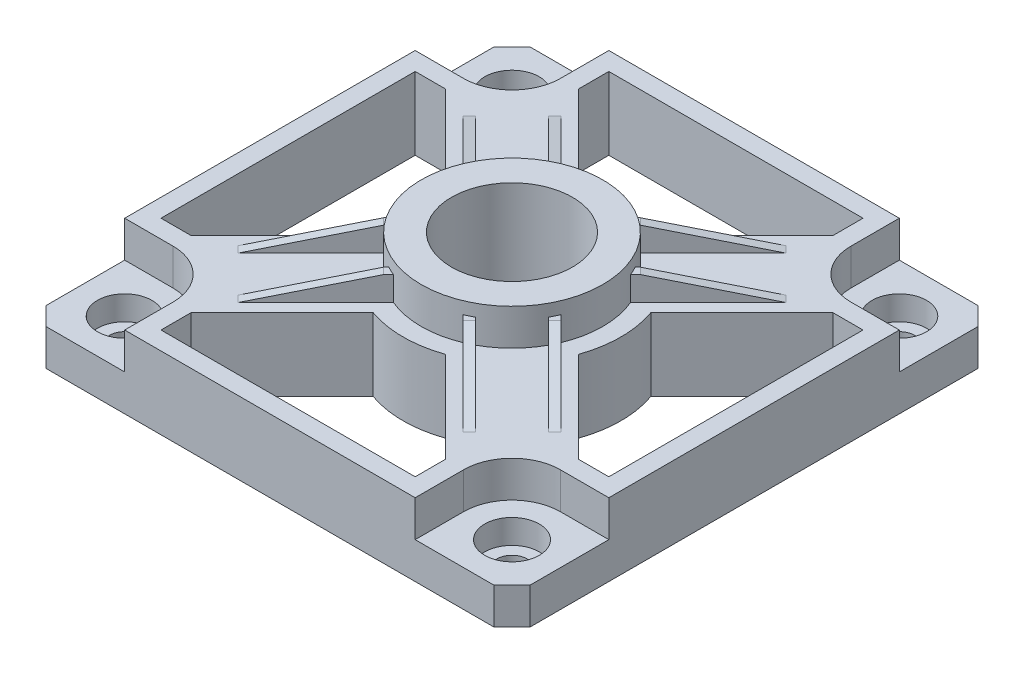
SolidWorks part; units mm, degrees
ref_plane "Front Plane" through (0, 0, 0) normal (0, 0, 1) x (1, 0, 0)
ref_plane "Top Plane" through (0, 0, 0) normal (0, 1, 0) x (1, 0, 0)
ref_plane "Right Plane" through (0, 0, 0) normal (1, 0, 0) x (0, 0, -1)
sketch "Sketch1" plane through (0, 0, 0) normal (0, 1, 0) x (1, 0, 0)
  line L1 (-40, 40) -> (40, 40)
  line L2 (-40, 40) -> (-40, -40)
  line L3 (-40, -40) -> (40, -40)
  line L4 (40, 40) -> (40, -40)
  line L5 (-40, 40) -> (40, -40) construction
  line L6 (-40, -40) -> (40, 40) construction
  point P0 (0, 0)
  dimension "D1" = 80
  dimension "D2" = 80
extrude "Boss-Extrude1" add sketch "Sketch1" along normal blind 12
chamfer "Chamfer1" distance 3 angle 45 4 edges at (-40, 6, 40) (-40, 6, -40) (40, 6, -40) (40, 6, 40)
sketch "Sketch2" plane through (0, 12, 0) normal (0, 1, 0) x (1, 0, 0)
  line L0 (-40, -24) -> (-32, -24)
  line L1 (-40, 37) -> (-40, -37) construction
  line L2 (-24, -32) -> (-24, -40)
  line L3 (-37, -40) -> (37, -40) construction
  line L4 (-24, -40) -> (-37, -40)
  line L5 (-37, -40) -> (-40, -37)
  line L6 (-40, -37) -> (-40, -24)
  arc A2 (-32, -24) -> (-24, -32) centre (-32, -32) cw
  dimension "D1" = 8
  dimension "D2" = 16
  dimension "D3" = 16
extrude "Cut-Extrude1" cut sketch "Sketch2" against normal blind 6
mirror "Mirror1" about plane through (0, 0, 0) normal (1, 0, 0) of "Cut-Extrude1"
mirror "Mirror2" about plane through (0, 0, 0) normal (0, 0, 1) of "Cut-Extrude1", "Mirror1"
hole_wizard "Hole3" positions "Sketch7" profile "Sketch8" legacy end condition up to next
sketch "Sketch7" plane through (0, 6, 0) normal (0, 1, 0) x (1, 0, 0)
  point P0 (-32, -32)
  point P3 (32, -32)
  point P6 (32, 32)
  point P9 (-32, 32)
sketch "Sketch8" plane through (-32, 6, 32) normal (1, 0, 0) x (0, 0, 1)
  line L0 (0, 0) -> (0, 6)
  line L1 (0, 6) -> (2.5, 6)
  line L2 (2.5, 6) -> (2.5, 4)
  line L3 (2.5, 4) -> (4.5, 4)
  line L4 (4.5, 4) -> (4.5, 0)
  line L5 (4.5, 0) -> (0, 0)
  line L6 (0, 110) -> (0, -10) construction
  dimension "Diameter" = 5
  dimension "Depth" = 6
  dimension "C-Bore Diameter" = 9
  dimension "C-Bore Depth" = 4
sketch "Sketch9" plane through (0, 12, 0) normal (0, 1, 0) x (1, 0, 0)
  circle A0 centre (0, 0) radius 15
  dimension "D1" = 30
extrude "Boss-Extrude2" add sketch "Sketch9" along normal blind 6
sketch "Sketch10" plane through (0, 18, 0) normal (0, 1, 0) x (1, 0, 0)
  line L0 (0, 0) -> (0, 34.9152) construction
  line L1 (-21, 37) -> (-21, 32)
  line L2 (-21, 32) -> (-5.9782, 16.9782)
  line L4 (21, 37) -> (21, 32)
  line L5 (21, 32) -> (5.9782, 16.9782)
  line L6 (-21, 37) -> (21, 37)
  line L9 (24, 40) -> (-24, 40) construction
  line L10 (24, 40) -> (24, 32) construction
  arc A1 (5.9782, 16.9782) -> (-5.9782, 16.9782) centre (0, 0) ccw
  point P9 (0, 11.3838)
  point P14 (0, 10.7272)
  point P15 (0, 10.946)
  dimension "D1" = 36
  dimension "D2" = 3
  dimension "D3" = 3
  dimension "D4" = 90
extrude "Cut-Extrude2" cut sketch "Sketch10" against normal through all
pattern_circular "CirPattern1" count 4 over 360 about axis through (0, 0, 0) along (0, 1, 0) of "Cut-Extrude2"
ref_plane "Plane1" through (0, 0, 0) normal (0.7071, 0, 0.7071) x (0.7071, 0, -0.7071)
sketch "Sketch12" plane through (0, 0, 0) normal (0.7071, 0, 0.7071) x (0.7071, 0, -0.7071)
  line L0 (11.3137, 12) -> (45.2548, 12) construction
  line L1 (15, 18) -> (-15, 18) construction
  line L2 (12, 12) -> (32, 12)
  line L3 (12, 12) -> (12, 16)
  line L4 (15, 12) -> (15, 18) construction
  line L5 (12, 16) -> (15, 16)
  line L6 (15, 16) -> (32, 12)
  point P6 (0, 0)
  dimension "D1" = 3
  dimension "D2" = 20
  dimension "D3" = 2
extrude "Boss-Extrude3" add sketch "Sketch12" along normal mid plane 1.5 from offset 5
mirror "Mirror4" about plane through (0, 0, 0) normal (0.7071, 0, 0.7071) of "Boss-Extrude3"
pattern_circular "CirPattern2" count 4 over 360 about axis through (0, 0, 0) along (0, 1, 0) of "Boss-Extrude3", "Mirror4"
hole_wizard "Hole4" positions "Sketch13" profile "Sketch14" legacy end condition up to next
sketch "Sketch13" plane through (0, 18, 0) normal (0, 1, 0) x (1, 0, 0)
  point P0 (0, 0)
sketch "Sketch14" plane through (0, 18, 0) normal (1, 0, 0) x (0, 0, 1)
  line L0 (0, 0) -> (0, 18)
  line L1 (0, 18) -> (10, 18)
  line L2 (10, 18) -> (10, 0)
  line L3 (10, 0) -> (0, 0)
  line L4 (0, 110) -> (0, -10) construction
  dimension "Diameter" = 20
  dimension "Depth" = 18
